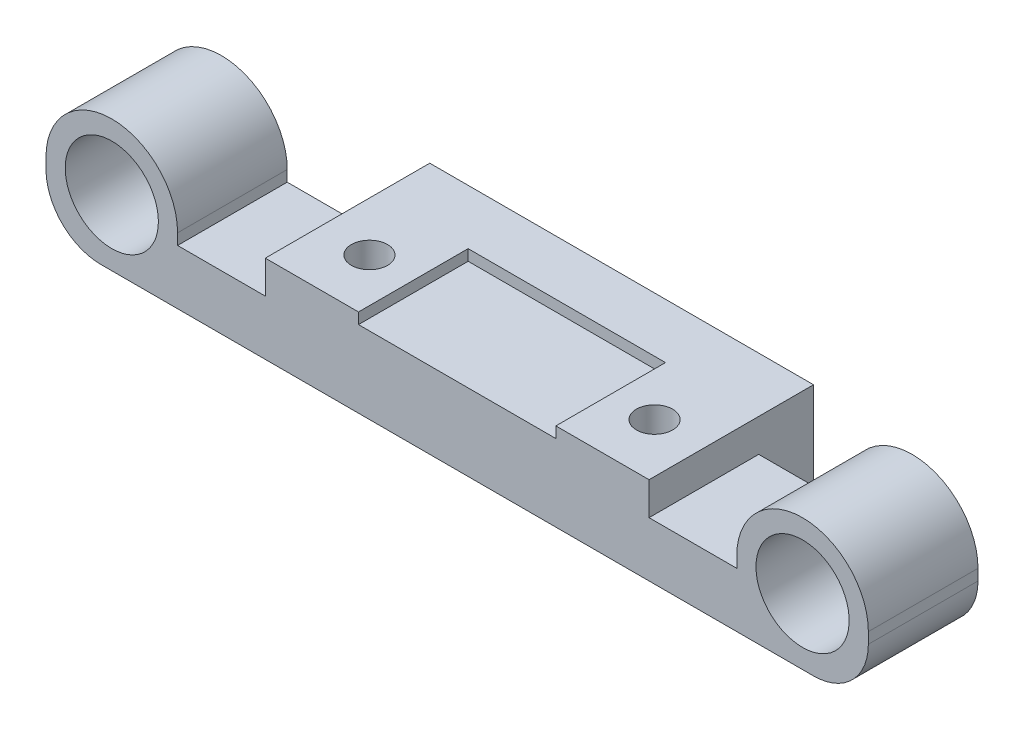
SolidWorks part; units mm, degrees
ref_plane "Front Plane" through (0, 0, 0) normal (0, 0, 1) x (1, 0, 0)
ref_plane "Top Plane" through (0, 0, 0) normal (0, 1, 0) x (1, 0, 0)
ref_plane "Right Plane" through (0, 0, 0) normal (1, 0, 0) x (0, 0, -1)
sketch "Sketch2" plane through (0, 0, 0) normal (0, 1, 0) x (1, 0, 0)
  line L5 (-8.5, -1.375) -> (8.5, -1.375)
  line L6 (-8.5, -1.375) -> (-8.5, 1.375)
  line L11 (-8.5, 1.375) -> (8.5, 1.375)
  line L12 (8.5, -1.375) -> (8.5, 1.375)
  line L13 (-8.5, -1.375) -> (8.5, 1.375) construction
  line L14 (-8.5, 1.375) -> (8.5, -1.375) construction
  point P0 (0, 0)
  dimension "D1" = 2.75
  dimension "D2" = 17
sketch "Sketch3" plane through (0, 0, 0) normal (0, 1, 0) x (1, 0, 0)
  line L0 (4, -9.375) -> (17.5, -9.375)
  line L1 (0, -5.375) -> (0, 0) construction
  line L2 (-8.5, -1.375) -> (8.5, -1.375) construction
  line L4 (-4, -9.375) -> (-4, -1.375)
  line L5 (-4, -1.375) -> (4, -1.375)
  line L6 (4, -9.375) -> (4, -1.375)
  line L7 (-4, -9.375) -> (4, -1.375) construction
  line L8 (-4, -1.375) -> (4, -9.375) construction
  line L11 (-17.5, -24.375) -> (17.5, -24.375)
  line L12 (-17.5, -24.375) -> (-17.5, -9.375)
  line L13 (-17.5, -9.375) -> (-4, -9.375)
  line L14 (17.5, -24.375) -> (17.5, -9.375)
  line L15 (-17.5, -24.375) -> (17.5, -9.375) construction
  line L16 (-17.5, -9.375) -> (17.5, -24.375) construction
  dimension "D1" = 8
  dimension "D2" = 8
  dimension "D3" = 35
  dimension "D4" = 15
extrude "Boss-Extrude1" add sketch "Sketch2" along normal blind 8 contours L11 L12 L5 L6
extrude "Boss-Extrude3" add sketch "Sketch3" along normal blind 8 contours L11 L14 L0 L6 L5 L4 L13 L12
sketch "Sketch5" plane through (0, 0, 0) normal (0, -1, 0) x (1, 0, 0)
  line L0 (-13, 19.375) -> (13, 19.375) construction
  line L2 (0, 0) -> (0, 19.375) construction
  line L3 (-17.5, 24.375) -> (17.5, 24.375) construction
  circle A0 centre (13, 19.375) radius 3
  circle A1 centre (-13, 19.375) radius 3
  dimension "D1" = 6
  dimension "D2" = 26
  dimension "D3" = 5
extrude "Cut-Extrude1" cut sketch "Sketch5" against normal blind 3 contours A1 | A0
sketch "Sketch6" plane through (0, 0, 0) normal (0, -1, 0) x (1, 0, 0)
  circle A0 centre (-13, 19.375) radius 1.65
  circle A1 centre (13, 19.375) radius 1.65
  dimension "D1" = 3.3
  dimension "D2" = 3.3
extrude "Cut-Extrude2" cut sketch "Sketch6" against normal blind 8
fillet "Fillet14" radius 2 1 edges at (-4, 4, 9.375)
fillet "Fillet15" radius 2 1 edges at (4, 4, 9.375)
fillet "Fillet16" radius 2 1 edges at (-4, 4, 1.375)
sketch "Sketch7" plane through (0, 8, 0) normal (0, 1, 0) x (1, 0, 0)
  line L0 (-17.5, -24.375) -> (17.5, -24.375) construction
  line L1 (-9, -14.375) -> (9, -14.375)
  line L2 (-9, -14.375) -> (-9, -24.375)
  line L3 (-9, -24.375) -> (9, -24.375)
  line L4 (9, -14.375) -> (9, -24.375)
  line L5 (0, 0) -> (0, -14.375) construction
  dimension "D1" = 18
  dimension "D2" = 10
extrude "Cut-Extrude3" cut sketch "Sketch7" against normal blind 1
fillet "Fillet18" radius 1.4 4 edges at (-8.5, 0, 0) (-8.5, 8, 0) (8.5, 8, 0) (8.5, 0, 0)
sketch "Sketch9" plane through (0, 0, 24.375) normal (0, 0, 1) x (1, 0, 0)
  line L0 (-17.5, 0) -> (-37.5, 0)
  line L1 (-37.5, 0) -> (-37.5, 6)
  line L3 (-17.5, 8) -> (-17.5, 0) construction
  line L4 (-17.5, 5) -> (-17.5, 0)
  line L5 (0, 0) -> (0, 8) construction
  line L6 (9, 8) -> (-9, 8) construction
  line L11 (-25.5, 6) -> (-25.5, 5)
  line L12 (-25.5, 5) -> (-17.5, 5)
  line L13 (-25.5, 6) -> (-37.5, 6) construction
  line L14 (25.5, 6) -> (25.5, 5)
  line L15 (37.5, 0) -> (37.5, 6)
  line L16 (17.5, 0) -> (37.5, 0)
  line L17 (17.5, 5) -> (17.5, 0)
  line L18 (25.5, 5) -> (17.5, 5)
  arc A0 (-37.5, 6) -> (-25.5, 6) centre (-31.5, 6) cw
  arc A2 (37.5, 6) -> (25.5, 6) centre (31.5, 6) ccw
  dimension "D3" = 6
  dimension "D1" = 1
  dimension "D2" = 20
  dimension "D4" = 5
extrude "Boss-Extrude4" add sketch "Sketch9" against normal blind 10
sketch "Sketch10" plane through (0, 0, 24.375) normal (0, 0, 1) x (1, 0, 0)
  line L0 (0, -4.4) -> (0, 4.4) construction
  circle A0 centre (-31.5, 6) radius 4.25
  circle A1 centre (31.5, 6) radius 4.25
  dimension "D1" = 8.5
extrude "Cut-Extrude4" cut sketch "Sketch10" against normal blind 8
fillet "Fillet17" radius 2 1 edges at (4, 4, 1.375)
fillet "Fillet19" radius 5 2 edges at (37.5, 0, 19.375) (-37.5, 0, 19.375)
sketch "Sketch11" plane through (0, 8, 0) normal (0, 1, 0) x (1, 0, 0)
  line L0 (-17.5, -9.375) -> (-6, -9.375) construction
  line L1 (-17.5, 4.1776) -> (17.5, 4.1776)
  line L2 (-17.5, 4.1776) -> (-17.5, -9.375)
  line L3 (-17.5, -9.375) -> (17.5, -9.375)
  line L4 (17.5, 4.1776) -> (17.5, -9.375)
extrude "Cut-Extrude5" cut sketch "Sketch11" against normal through all
